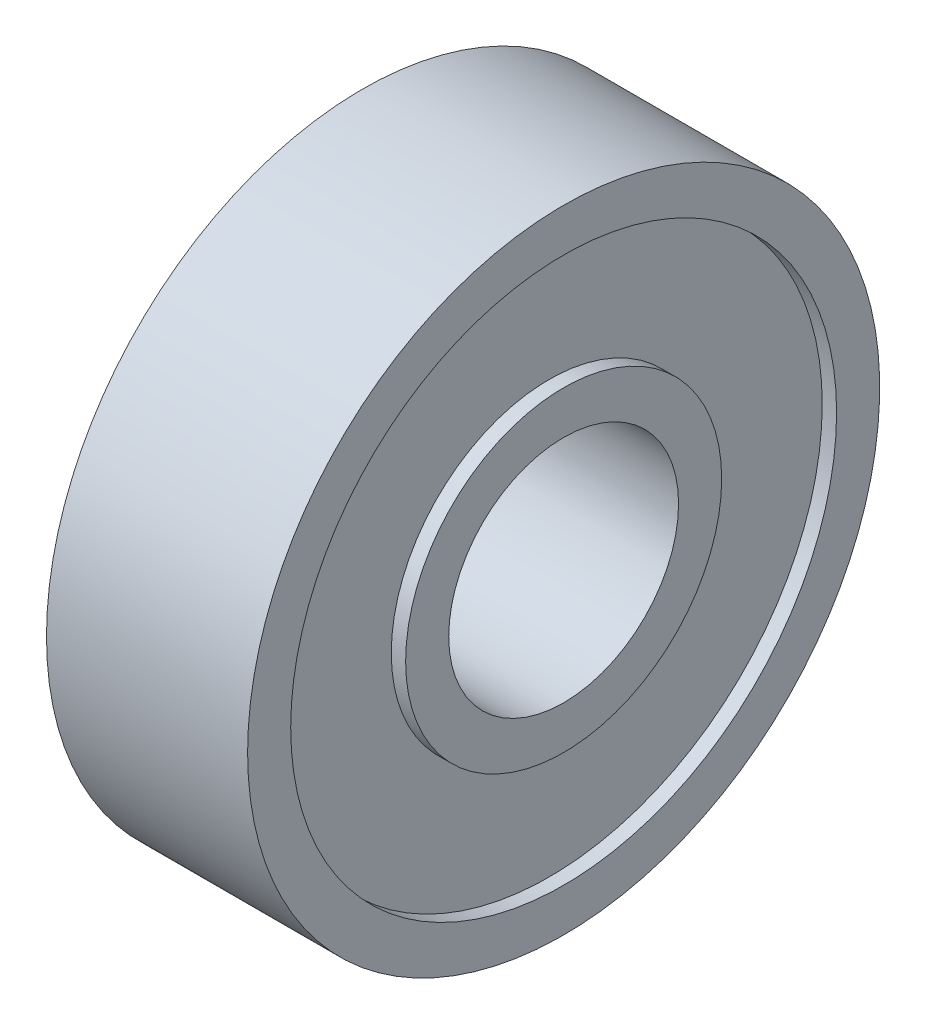
SolidWorks part; units mm, degrees
ref_plane "Alzado" through (0, 0, 0) normal (0, 0, 1) x (1, 0, 0)
ref_plane "Planta" through (0, 0, 0) normal (0, 1, 0) x (1, 0, 0)
ref_plane "Vista lateral" through (0, 0, 0) normal (1, 0, 0) x (0, 0, -1)
sketch "Croquis1" plane through (0, 0, 0) normal (0, 0, 1) x (1, 0, 0)
  line L0 (0, 0) -> (0, 11) construction
  line L1 (-3.5, 11) -> (3.5, 11)
  line L2 (3.5, 11) -> (3.5, 9.5)
  line L3 (3.5, 9.5) -> (3, 9.5)
  line L4 (3, 9.5) -> (3, 5.5)
  line L5 (3, 5.5) -> (3.5, 5.5)
  line L6 (3.5, 5.5) -> (3.5, 4)
  line L7 (3.5, 4) -> (-3.5, 4)
  line L8 (-3.5, 5.5) -> (-3.5, 4)
  line L9 (-3, 5.5) -> (-3.5, 5.5)
  line L10 (-3, 9.5) -> (-3, 5.5)
  line L11 (-3.5, 9.5) -> (-3, 9.5)
  line L12 (-3.5, 11) -> (-3.5, 9.5)
  line L13 (-3.5, 0) -> (3.5, 0) construction
  dimension "D1" = 11
  dimension "D2" = 4
  dimension "D3" = 1.5
  dimension "D4" = 0.5
  dimension "D5" = 7
revolve "Revolución1" add sketch "Croquis1" angle 360 about L13
